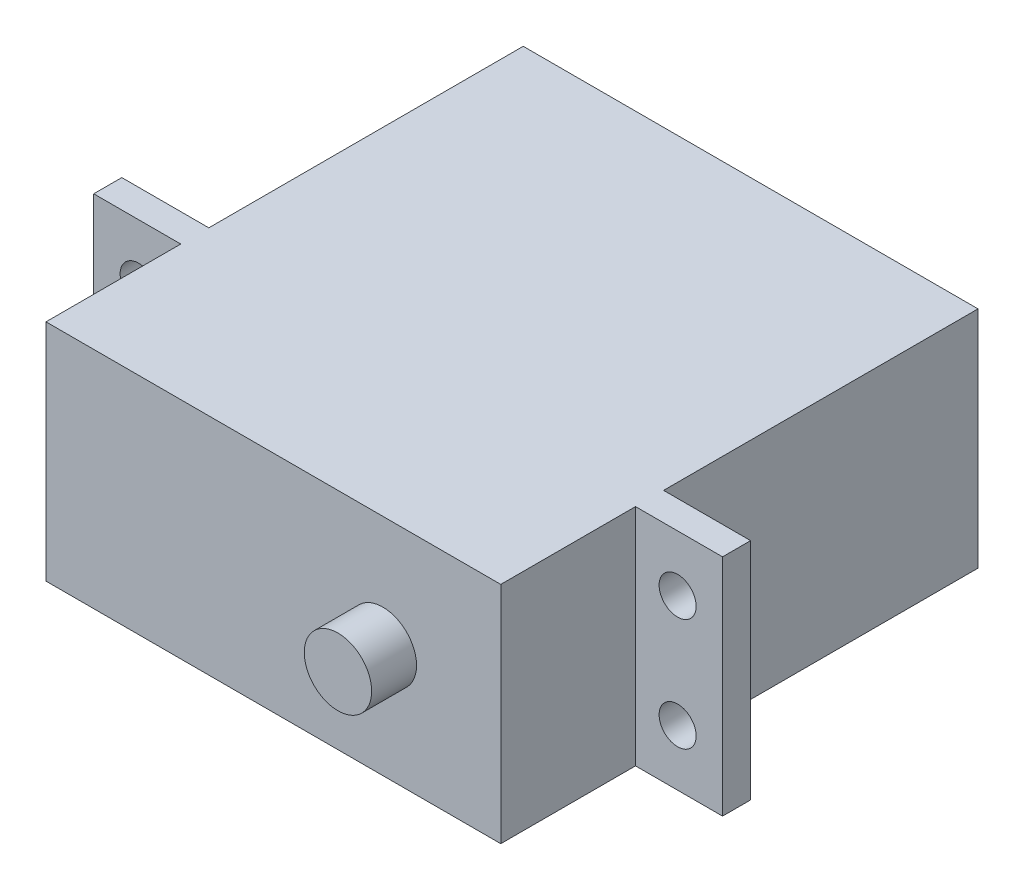
SolidWorks part; units mm, degrees
ref_plane "前视基准面" through (0, 0, 0) normal (0, 0, 1) x (1, 0, 0)
ref_plane "上视基准面" through (0, 0, 0) normal (0, 1, 0) x (1, 0, 0)
ref_plane "右视基准面" through (0, 0, 0) normal (1, 0, 0) x (0, 0, -1)
sketch "草图1" plane through (0, 0, 0) normal (0, 0, 1) x (1, 0, 0)
  line L1 (0, 0) -> (40.5, 0)
  line L2 (0, 0) -> (0, -20)
  line L3 (0, -20) -> (40.5, -20)
  line L4 (40.5, 0) -> (40.5, -20)
  dimension "D1" = 40.5
  dimension "D2" = 20
extrude "凸台-拉伸1" add sketch "草图1" along normal blind 28
sketch "草图2" plane through (0, 0, 28) normal (0, 0, 1) x (1, 0, 0)
  line L1 (-7.75, 0) -> (48.25, 0)
  line L2 (-7.75, 0) -> (-7.75, -20)
  line L3 (-7.75, -20) -> (48.25, -20)
  line L4 (0, 0) -> (0, -20)
  line L5 (0, -20) -> (40.5, -20)
  line L6 (40.5, -20) -> (40.5, 0)
  line L7 (40.5, 0) -> (0, 0)
  line L8 (0, 0) -> (0, -20)
  line L9 (0, -20) -> (40.5, -20)
  line L10 (40.5, -20) -> (40.5, 0)
  line L11 (40.5, 0) -> (0, 0)
  line L12 (48.25, 0) -> (48.25, -20)
  point P8 (20.25, 0)
  point P9 (20.25, 0)
  line M9 (0, 0) -> (0, -20)
  line M10 (0, -20) -> (40.5, -20)
  line M11 (40.5, -20) -> (40.5, 0)
  line M12 (40.5, 0) -> (0, 0)
  dimension "D2" = 56
  dimension "D3" = 20
  dimension "D1" = 0
extrude "凸台-拉伸2" add sketch "草图2" along normal blind 2.5 contours L2 L3 L1 M9 | M12 M9 M10 M11 | L12 L1 L3 M11
sketch "草图3" plane through (0, 0, 30.5) normal (0, 0, 1) x (1, 0, 0)
  line L1 (0, 0) -> (40.5, 0)
  line L2 (0, 0) -> (0, -20)
  line L3 (0, -20) -> (40.5, -20)
  line L4 (-7.75, 0) -> (-7.75, -20)
  line L5 (-7.75, -20) -> (48.25, -20)
  line L6 (48.25, -20) -> (48.25, 0)
  line L7 (48.25, 0) -> (-7.75, 0)
  line L8 (-7.75, 0) -> (-7.75, -20)
  line L9 (-7.75, -20) -> (48.25, -20)
  line L10 (48.25, -20) -> (48.25, 0)
  line L11 (48.25, 0) -> (-7.75, 0)
  line L12 (40.5, 0) -> (40.5, -20)
  point P8 (20.25, 0)
  point P9 (20.25, 0)
  line M10 (-7.75, -20) -> (48.25, -20)
  line M12 (48.25, 0) -> (-7.75, 0)
  dimension "D2" = 40.5
  dimension "D3" = 20
  dimension "D1" = 0
extrude "凸台-拉伸3" add sketch "草图3" along normal blind 12 contours L12 L2 M12 M10
sketch "草图4" plane through (0, 0, 42.5) normal (0, 0, 1) x (1, 0, 0)
  line L4 (40.5, -20) -> (40.5, 0)
  line L5 (40.5, 0) -> (0, 0)
  line L6 (0, 0) -> (0, -20)
  line L7 (0, -20) -> (40.5, -20)
  line L8 (40.5, -20) -> (40.5, 0)
  line L9 (40.5, 0) -> (0, 0)
  line L10 (0, 0) -> (0, -20)
  line L11 (0, -20) -> (40.5, -20)
  circle A0 centre (30, -10) radius 3
  point P7 (40.5, -10)
  dimension "D2" = 6
  dimension "D3" = 30
  dimension "D1" = 0
extrude "凸台-拉伸4" add sketch "草图4" along normal blind 4 contours A0
sketch "草图5" plane through (0, 0, 30.5) normal (0, 0, 1) x (1, 0, 0)
  line L0 (20.25, 7.3672) -> (20.25, -24.215) construction
  line L1 (0, -20) -> (40.5, -20) construction
  line L2 (0, -20) -> (40.5, -20)
  line L3 (-13.6357, -10) -> (50.2603, -10) construction
  line L4 (0, -20) -> (0, 0)
  line L5 (0, 0) -> (-7.75, 0)
  line L6 (-7.75, 0) -> (-7.75, -20)
  line L7 (-7.75, -20) -> (0, -20)
  line L8 (0, -20) -> (0, 0)
  line L9 (0, 0) -> (-7.75, 0)
  line L10 (-7.75, 0) -> (-7.75, -20)
  line L11 (-7.75, -20) -> (0, -20)
  line L12 (48.25, 0) -> (40.5, 0)
  line L13 (40.5, 0) -> (40.5, -20)
  line L14 (40.5, -20) -> (48.25, -20)
  line L15 (48.25, -20) -> (48.25, 0)
  line L16 (48.25, 0) -> (40.5, 0)
  line L17 (40.5, 0) -> (40.5, -20)
  line L18 (40.5, -20) -> (48.25, -20)
  line L19 (48.25, -20) -> (48.25, 0)
  circle A0 centre (-3.75, -5) radius 1.65
  circle A1 centre (-3.75, -15) radius 1.65
  circle A2 centre (44.25, -15) radius 1.65
  circle A3 centre (44.25, -5) radius 1.65
  point P12 (20.25, -20)
  point P17 (48.25, -10)
  dimension "D3" = 3.3
  dimension "D4" = 10
  dimension "D5" = 48
  dimension "D1" = 0
  dimension "D2" = 0
extrude "切除-拉伸1" cut sketch "草图5" against normal through all contours A0 | A1 | A3 | A2
